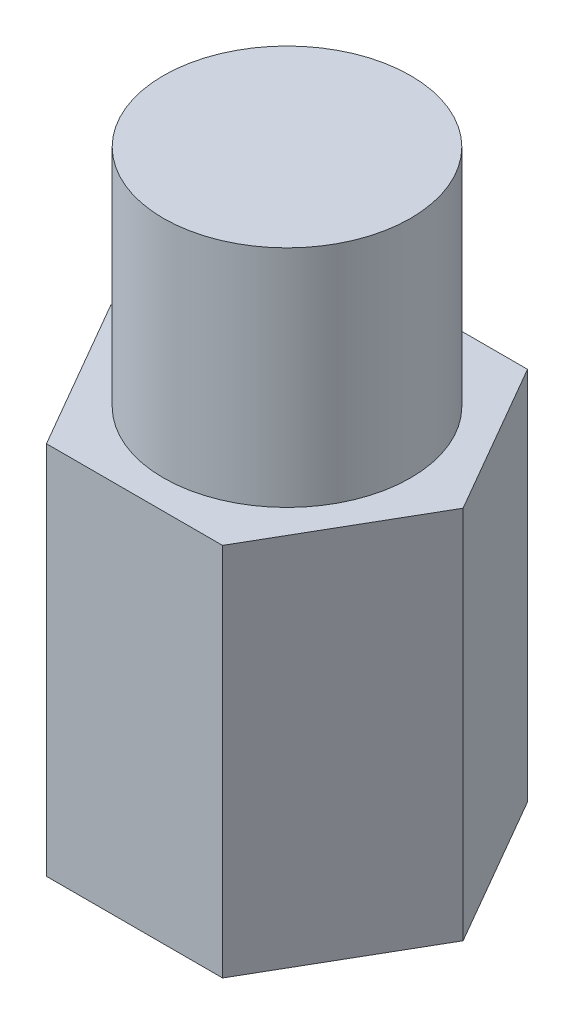
SolidWorks part; units mm, degrees
ref_plane "前视基准面" through (0, 0, 0) normal (0, 0, 1) x (1, 0, 0)
ref_plane "上视基准面" through (0, 0, 0) normal (0, 1, 0) x (1, 0, 0)
ref_plane "右视基准面" through (0, 0, 0) normal (1, 0, 0) x (0, 0, -1)
sketch "草图1" plane through (0, 0, 0) normal (0, 1, 0) x (1, 0, 0)
  line L1 (1.175, -2.0352) -> (2.35, 0)
  line L2 (2.35, 0) -> (1.175, 2.0352)
  line L3 (1.175, 2.0352) -> (-1.175, 2.0352)
  line L4 (-1.175, 2.0352) -> (-2.35, 0)
  line L5 (-2.35, 0) -> (-1.175, -2.0352)
  line L6 (-1.175, -2.0352) -> (1.175, -2.0352)
  circle A0 centre (0, 0) radius 2.0352 construction
  point P1 (26.3084, 0)
  point P10 (11.2147, 19.4244)
  dimension "D1" = 4.7
extrude "凸台-拉伸1" add sketch "草图1" along normal blind 5
sketch "草图2" plane through (0, 5, 0) normal (0, 1, 0) x (1, 0, 0)
  circle A0 centre (0, 0) radius 1.65
  dimension "D1" = 3.3
extrude "凸台-拉伸2" add sketch "草图2" along normal blind 3
sketch "草图3" plane through (0, 0, 0) normal (0, -1, 0) x (1, 0, 0)
  circle A0 centre (0, 0) radius 1.65
  dimension "D1" = 3.3
extrude "切除-拉伸1" cut sketch "草图3" against normal blind 3
